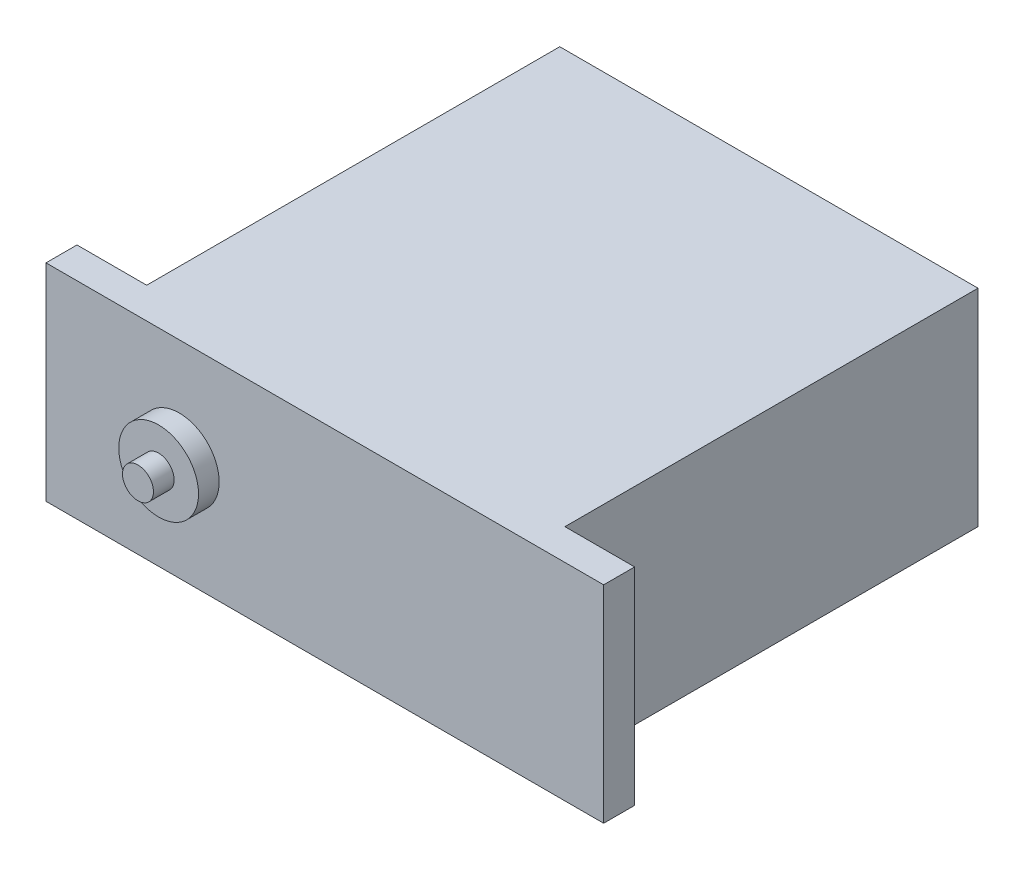
SolidWorks part; units mm, degrees
ref_plane "前视基准面" through (0, 0, 0) normal (0, 0, 1) x (1, 0, 0)
ref_plane "上视基准面" through (0, 0, 0) normal (0, 1, 0) x (1, 0, 0)
ref_plane "右视基准面" through (0, 0, 0) normal (1, 0, 0) x (0, 0, -1)
sketch "草图1" plane through (0, 0, 0) normal (0, 0, 1) x (1, 0, 0)
  line L1 (-20.25, -10) -> (20.25, -10)
  line L2 (-20.25, -10) -> (-20.25, 10)
  line L3 (-20.25, 10) -> (20.25, 10)
  line L4 (20.25, -10) -> (20.25, 10)
  line L5 (-20.25, -10) -> (20.25, 10) construction
  line L6 (-20.25, 10) -> (20.25, -10) construction
  point P0 (0, 0)
  dimension "D1" = 40.5
  dimension "D2" = 20
extrude "凸台-拉伸1" add sketch "草图1" along normal blind 40
sketch "草图2" plane through (0, 0, 40) normal (0, 0, 1) x (1, 0, 0)
  line L1 (-27, -10) -> (27, -10)
  line L2 (-27, -10) -> (-27, 10)
  line L3 (-27, 10) -> (27, 10)
  line L4 (27, -10) -> (27, 10)
  line L5 (-27, -10) -> (27, 10) construction
  line L6 (-27, 10) -> (27, -10) construction
  point P0 (0, 0)
  dimension "D1" = 20
  dimension "D2" = 54
extrude "凸台-拉伸2" add sketch "草图2" along normal blind 3
sketch "草图3" plane through (0, 0, 43) normal (0, 0, 1) x (1, 0, 0)
  circle A0 centre (-14.0925, 0) radius 3.863
extrude "凸台-拉伸3" add sketch "草图3" along normal blind 2
sketch "草图4" plane through (0, 0, 45) normal (0, 0, 1) x (1, 0, 0)
  circle A0 centre (-14.0925, 0) radius 1.5
  dimension "D1" = 3
extrude "凸台-拉伸4" add sketch "草图4" along normal blind 2
